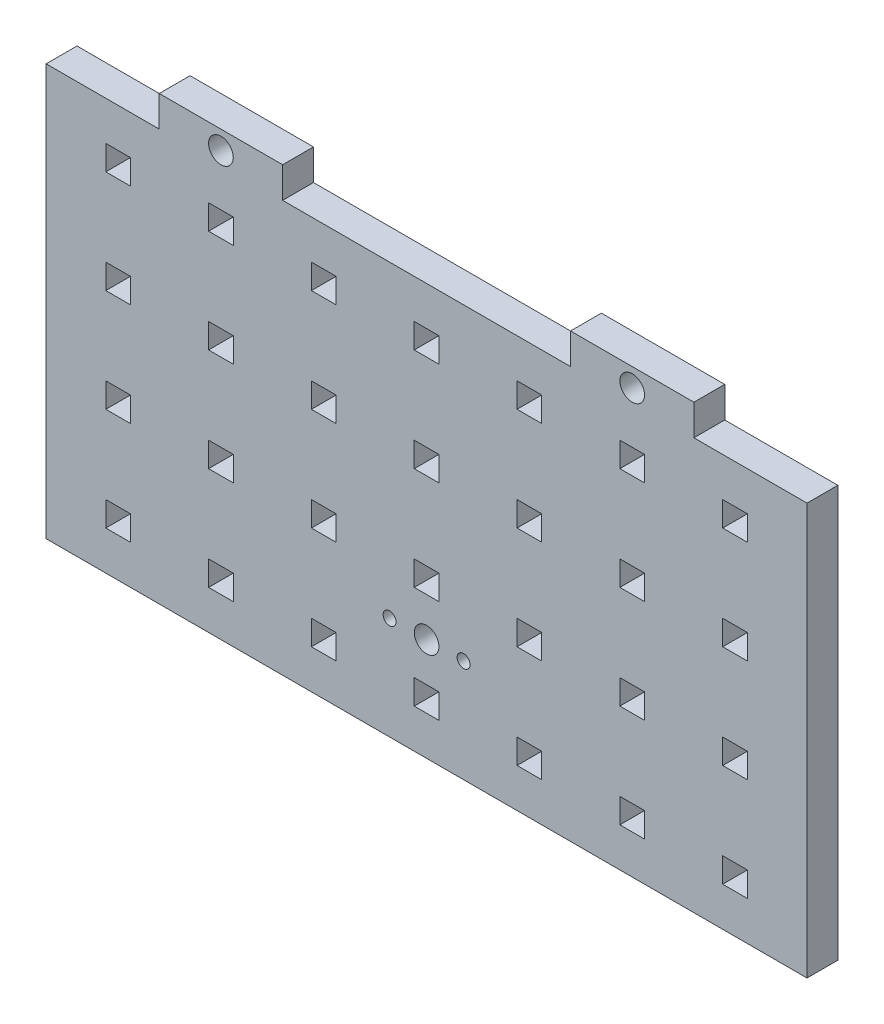
SolidWorks part; units mm, degrees
ref_plane "Front Plane" through (0, 0, 0) normal (0, 0, 1) x (1, 0, 0)
ref_plane "Top Plane" through (0, 0, 0) normal (0, 1, 0) x (1, 0, 0)
ref_plane "Right Plane" through (0, 0, 0) normal (1, 0, 0) x (0, 0, -1)
sketch "Sketch1" plane through (0, 0, 0) normal (0, 0, 1) x (1, 0, 0)
  line L0 (46.99, 0) -> (-46.99, 0) construction
  line L1 (-46.99, -25.4) -> (46.99, -25.4)
  line L2 (-46.99, -25.4) -> (-46.99, 25.4)
  line L3 (-46.99, 25.4) -> (46.99, 25.4)
  line L4 (46.99, -25.4) -> (46.99, 25.4)
  line L5 (0, 25.4) -> (0, -25.4) construction
  point P22 (0, 0)
  dimension "D1" = 50.8
  dimension "D2" = 93.98
  dimension "D3" = 25.4
extrude "Boss-Extrude4" add sketch "Sketch1" along normal blind 3.81
sketch "Sketch26" plane through (0, 0, 3.81) normal (0, 0, 1) x (1, 0, 0)
  line L1 (39.624, 17.526) -> (36.576, 17.526)
  line L2 (39.624, 17.526) -> (39.624, 20.574)
  line L3 (39.624, 20.574) -> (36.576, 20.574)
  line L4 (36.576, 17.526) -> (36.576, 20.574)
  point P4 (36.576, 19.05)
  point P6 (38.1, 17.526)
  dimension "D1" = 3.048
  dimension "D2" = 3.048
  dimension "D3" = 19.05
  dimension "D4" = 38.1
extrude "Cut-Extrude30" cut sketch "Sketch26" against normal through all
pattern_linear "LPattern9" count 4 spacing 12.7 along (0, -1, 0) count 7 spacing 12.7 along (-1, 0, 0) of "Cut-Extrude30"
sketch "Sketch25" plane through (0, 0, 3.81) normal (0, 0, 1) x (1, 0, 0)
  line L4 (0, 0) -> (0, -25.4) construction
  line L6 (-46.99, -25.4) -> (46.99, -25.4) construction
  circle A0 centre (0, -12.7) radius 1.524
  circle A1 centre (-4.572, -12.7) radius 0.8
  circle A2 centre (4.572, -12.7) radius 0.8
  dimension "D1" = 3.048
  dimension "D2" = 1.6
  dimension "D3" = 4.572
  dimension "D4" = 12.7
extrude "Cut-Extrude29" cut sketch "Sketch25" against normal through all
sketch "Sketch27" plane through (0, 0, 3.81) normal (0, 0, 1) x (1, 0, 0)
  line L0 (0, 22.7279) -> (0, 29.887) construction
  line L1 (33.02, 25.4) -> (33.02, 29.21)
  line L2 (46.99, 25.4) -> (-46.99, 25.4) construction
  line L3 (33.02, 29.21) -> (17.78, 29.21)
  line L4 (17.78, 29.21) -> (17.78, 25.4)
  line L5 (33.02, 25.4) -> (17.78, 25.4)
  point P7 (25.4, 29.21)
  dimension "D1" = 25.4
  dimension "D2" = 15.24
  dimension "D3" = 3.81
extrude "Boss-Extrude5" add sketch "Sketch27" against normal blind 3.81
sketch "Sketch28" plane through (0, 0, 3.81) normal (0, 0, 1) x (1, 0, 0)
  line L0 (33.02, 29.21) -> (17.78, 29.21) construction
  circle A0 centre (25.4, 26.924) radius 1.524
  point P4 (25.4, 29.21)
  dimension "D1" = 3.048
  dimension "D2" = 2.286
extrude "Cut-Extrude31" cut sketch "Sketch28" against normal through all
mirror "Mirror1" about plane through (0, 0, 0) normal (1, 0, 0) of "Boss-Extrude5", "Cut-Extrude31"
